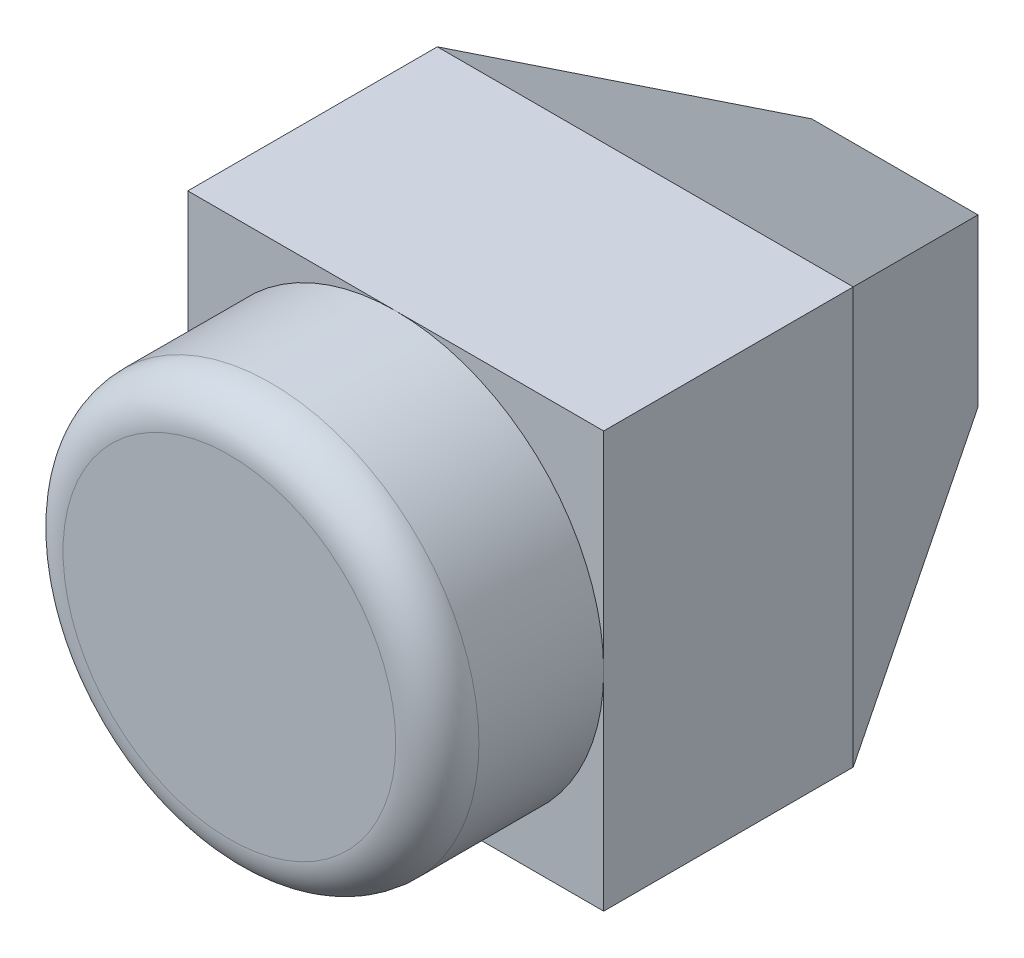
SolidWorks part; units mm, degrees
ref_plane "Piano frontale" through (0, 0, 0) normal (0, 0, 1) x (1, 0, 0)
ref_plane "Piano superiore" through (0, 0, 0) normal (0, 1, 0) x (1, 0, 0)
ref_plane "Piano destro" through (0, 0, 0) normal (1, 0, 0) x (0, 0, -1)
sketch "Schizzo1" plane through (0, 0, 0) normal (0, 0, 1) x (1, 0, 0)
  circle A0 centre (0, 0) radius 5
  dimension "D1" = 10
extrude "Estrusione-Estrusione1" add sketch "Schizzo1" along normal blind 4
sketch "Schizzo2" plane through (0, 0, 0) normal (0, 0, -1) x (-1, 0, 0)
  line L1 (-5, -5) -> (5, -5)
  line L2 (-5, -5) -> (-5, 5)
  line L3 (-5, 5) -> (5, 5)
  line L4 (5, -5) -> (5, 5)
  line L5 (0, 5) -> (0, -5) construction
  line L6 (-5, 0) -> (5, 0) construction
  point P0 (0, 0)
  dimension "D1" = 10
extrude "Estrusione-Estrusione2" add sketch "Schizzo2" along normal blind 12
fillet "Raccordo1" radius 1 1 edges at (5, 0, 4)
chamfer "Smusso1" distance 6 distance2 3 4 edges at (0, -5, -12) (5, 0, -12) (0, 5, -12) (-5, 0, -12)
